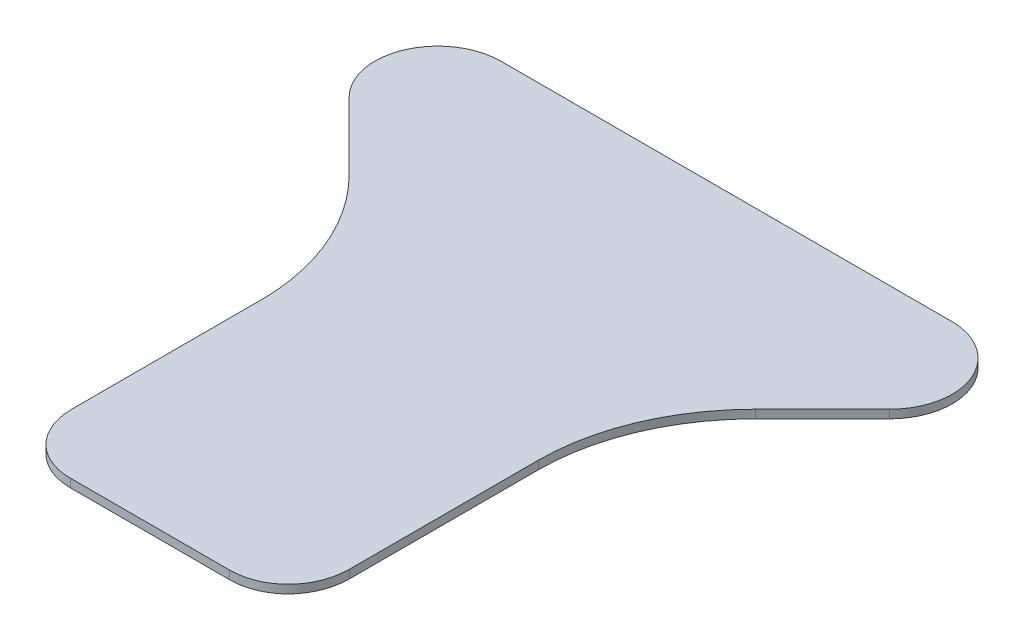
SolidWorks part; units mm, degrees
ref_plane "Front Plane" through (0, 0, 0) normal (0, 0, 1) x (1, 0, 0)
ref_plane "Top Plane" through (0, 0, 0) normal (0, 1, 0) x (1, 0, 0)
ref_plane "Right Plane" through (0, 0, 0) normal (1, 0, 0) x (0, 0, -1)
sketch "Sketch2" plane through (0, 0, 0) normal (0, 1, 0) x (1, 0, 0)
  line L10 (33.1269, -63.0937) -> (33.1269, -18.0547)
  line L11 (-18.9725, -77.6434) -> (18.9725, -77.6434)
  line L12 (-33.1269, -18.0547) -> (-33.1269, -63.0937)
  line L13 (-64.532, 34.4338) -> (-48.5023, 18.404)
  line L14 (53.804, 60) -> (-53.804, 60)
  line L15 (48.5023, 18.404) -> (64.532, 34.4338)
  line L22 (33.1269, -63.0937) -> (33.1269, -18.0547)
  line L23 (-18.9725, -77.6434) -> (18.9725, -77.6434)
  line L24 (-33.1269, -18.0547) -> (-33.1269, -63.0937)
  line L25 (-64.532, 34.4338) -> (-48.5023, 18.404)
  line L26 (53.804, 60) -> (-53.804, 60)
  line L27 (48.5023, 18.404) -> (64.532, 34.4338)
  ellipse E6 centre (17.5978, -61.6807) end of major axis (27.3567, -74.9368) minor radius 15 (18.9725, -77.6434) -> (33.1269, -63.0937) ccw
  ellipse E7 centre (-17.5978, -61.6807) end of major axis (-7.8389, -48.4246) minor radius 15 (-33.1269, -63.0937) -> (-18.9725, -77.6434) ccw
  ellipse E8 centre (-84.8907, -16.1883) end of major axis (-130.9116, 8.582) minor radius 50 (-33.1269, -18.0547) -> (-48.5023, 18.404) ccw
  ellipse E9 centre (-53.804, 45) end of major axis (-38.6897, 45) minor radius 15 (-53.804, 60) -> (-64.532, 34.4338) ccw
  ellipse E10 centre (53.804, 45) end of major axis (38.6897, 45) minor radius 15 (64.532, 34.4338) -> (53.804, 60) ccw
  ellipse E11 centre (84.8907, -16.1883) end of major axis (130.9116, 8.582) minor radius 50 (48.5023, 18.404) -> (33.1269, -18.0547) ccw
  ellipse E12 centre (17.5978, -61.6807) end of major axis (27.3567, -74.9368) minor radius 15 (18.9725, -77.6434) -> (33.1269, -63.0937) ccw
  ellipse E13 centre (-17.5978, -61.6807) end of major axis (-7.8389, -48.4246) minor radius 15 (-33.1269, -63.0937) -> (-18.9725, -77.6434) ccw
  ellipse E14 centre (-84.8907, -16.1883) end of major axis (-130.9116, 8.582) minor radius 50 (-33.1269, -18.0547) -> (-48.5023, 18.404) ccw
  ellipse E15 centre (-53.804, 45) end of major axis (-38.6897, 45) minor radius 15 (-53.804, 60) -> (-64.532, 34.4338) ccw
  ellipse E16 centre (53.804, 45) end of major axis (38.6897, 45) minor radius 15 (64.532, 34.4338) -> (53.804, 60) ccw
  ellipse E17 centre (84.8907, -16.1883) end of major axis (130.9116, 8.582) minor radius 50 (48.5023, 18.404) -> (33.1269, -18.0547) ccw
  dimension "D1" = 0
extrude "Boss-Extrude1" add sketch "Sketch2" against normal blind 2
